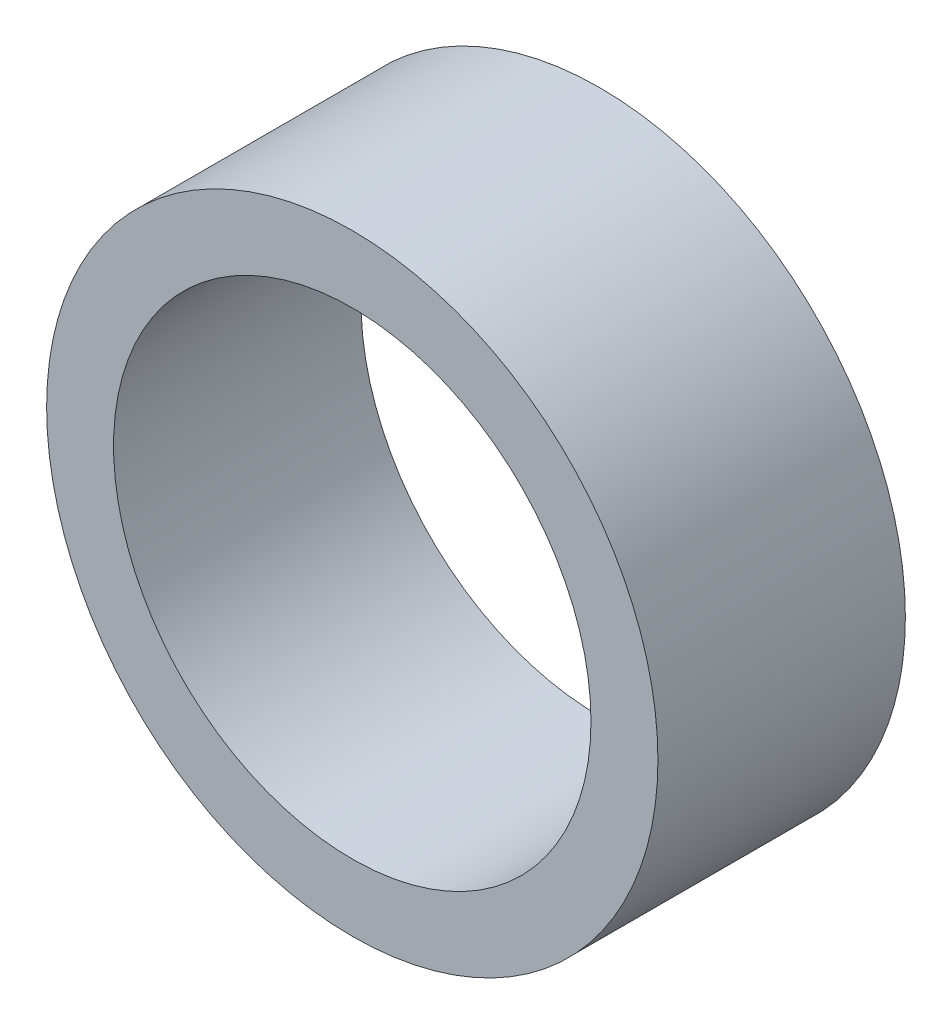
SolidWorks part; units mm, degrees
material "Malleable Cast Iron"
ref_plane "Front Plane" through (0, 0, 0) normal (0, 0, 1) x (1, 0, 0)
ref_plane "Top Plane" through (0, 0, 0) normal (0, 1, 0) x (1, 0, 0)
ref_plane "Right Plane" through (0, 0, 0) normal (1, 0, 0) x (0, 0, -1)
sketch "Sketch1" plane through (0, 0, 0) normal (0, 0, 1) x (1, 0, 0)
  circle A0 centre (0, 0) radius 10.5
  circle A1 centre (0, 0) radius 8.2
  dimension "D1" = 21
  dimension "D2" = 2.3
extrude "Boss-Extrude1" add sketch "Sketch1" along normal blind 8.5
